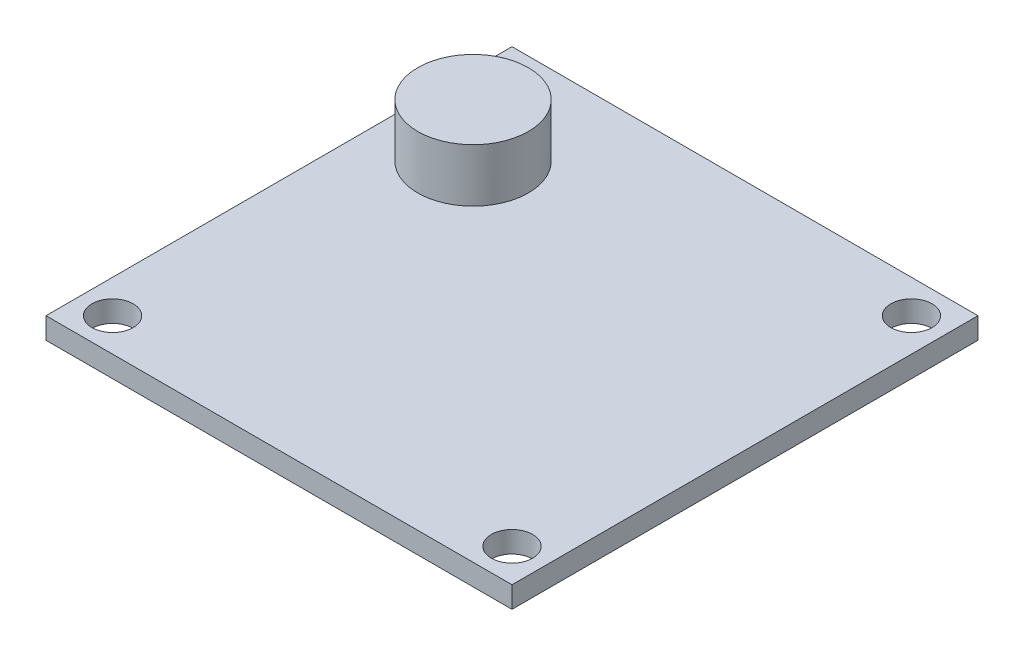
SolidWorks part; units mm, degrees
ref_plane "Front Plane" through (0, 0, 0) normal (0, 0, 1) x (1, 0, 0)
ref_plane "Top Plane" through (0, 0, 0) normal (0, 1, 0) x (1, 0, 0)
ref_plane "Right Plane" through (0, 0, 0) normal (1, 0, 0) x (0, 0, -1)
sketch "Sketch1" plane through (0, 0, 0) normal (0, 1, 0) x (1, 0, 0)
  line L0 (0, 17.5) -> (0, -17.5) construction
  line L1 (17.5, 17.5) -> (-17.5, 17.5)
  line L2 (17.5, 17.5) -> (17.5, -17.5)
  line L3 (17.5, -17.5) -> (-17.5, -17.5)
  line L4 (-17.5, 17.5) -> (-17.5, -17.5)
  line L5 (17.5, 17.5) -> (-17.5, -17.5) construction
  line L6 (17.5, -17.5) -> (-17.5, 17.5) construction
  line L7 (-17.5, 0) -> (17.5, 0) construction
  circle A0 centre (-15, 15) radius 1.55
  circle A1 centre (15, 15) radius 1.55
  circle A2 centre (15, -15) radius 1.55
  circle A3 centre (-15, -15) radius 1.55
  point P0 (0, 0)
  dimension "D3" = 3.1
  dimension "D4" = 30
  dimension "D1" = 35
  dimension "D2" = 35
extrude "Boss-Extrude1" add sketch "Sketch1" along normal blind 1.6
sketch "Sketch2" plane through (0, 1.6, 0) normal (0, 1, 0) x (1, 0, 0)
  circle A0 centre (-11.5212, 8.5955) radius 4.1543
extrude "Boss-Extrude2" add sketch "Sketch2" along normal blind 4
